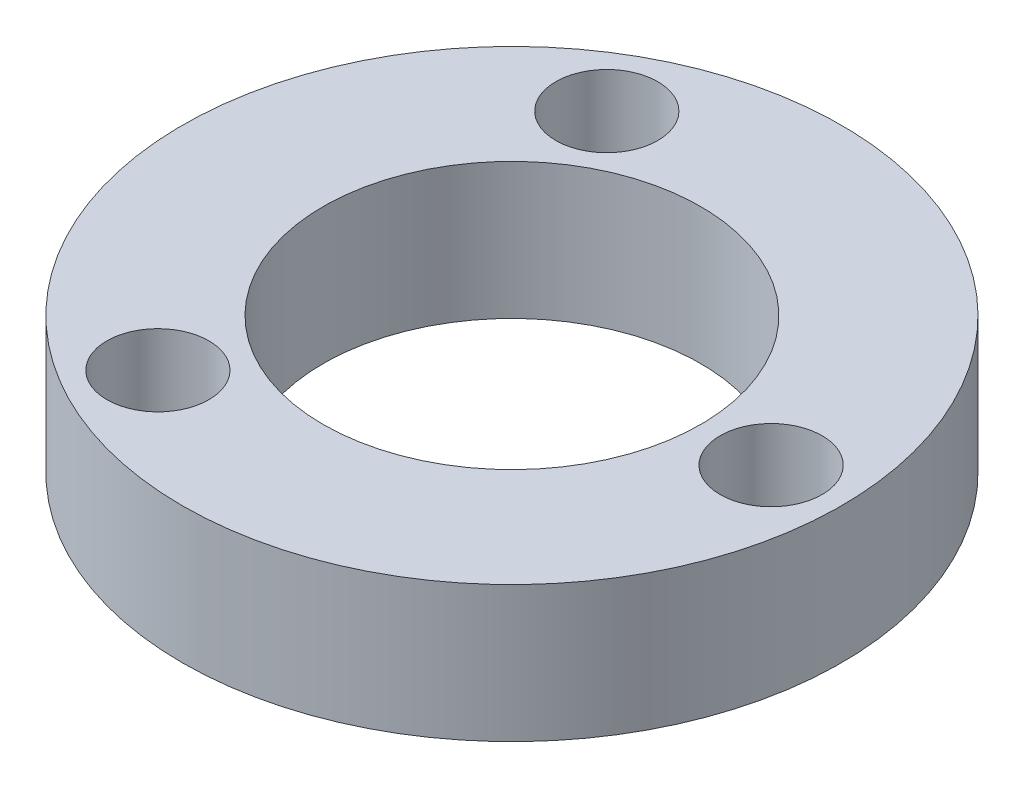
SolidWorks part; units mm, degrees
material "ABS"
ref_plane "Front Plane" through (0, 0, 0) normal (0, 0, 1) x (1, 0, 0)
ref_plane "Top Plane" through (0, 0, 0) normal (0, 1, 0) x (1, 0, 0)
ref_plane "Right Plane" through (0, 0, 0) normal (1, 0, 0) x (0, 0, -1)
sketch "Sketch1" plane through (0, 0, 0) normal (0, 1, 0) x (1, 0, 0)
  circle A2 centre (-9.5263, -16.4999) radius 3.175 construction
  circle A3 centre (-9.5262, 16.4999) radius 3.175 construction
  circle A4 centre (19.0525, 0) radius 3.175 construction
  circle A5 centre (-9.5262, 16.4999) radius 3.175
  circle A6 centre (19.0525, 0) radius 3.175
  circle A7 centre (-9.5263, -16.4999) radius 3.175
  circle A15 centre (0, 0) radius 13.8775
  circle A16 centre (0, 0) radius 24.2275
  point P1 (30.1365, 0)
  point P12 (-9.5263, -16.4999)
  point P14 (19.0525, 0)
  point P16 (-9.5262, 16.4999)
  point P20 (-4.9245, 20.2425)
  point P29 (-4.9245, -20.2425)
  dimension "D3" = 6.35
  dimension "D2" = 19.0525
extrude "Boss-Extrude1" add sketch "Sketch1" along normal blind 10
sketch "Sketch3" plane through (0, 10, 0) normal (0, 1, 0) x (1, 0, 0)
  circle A1 centre (19.0525, 0) radius 3.75
  dimension "D1" = 7.5
extrude "Cut-Extrude1" cut sketch "Sketch3" against normal blind 7.5
sketch "Sketch5" plane through (0, 0, 0) normal (0, 0, 1) x (1, 0, 0)
  line L0 (0, 0) -> (0, 1.348) construction
pattern_circular "CirPattern1" count 3 every 120 about axis through (0, 0, 0) along (0, 1, 0) of "Cut-Extrude1"
